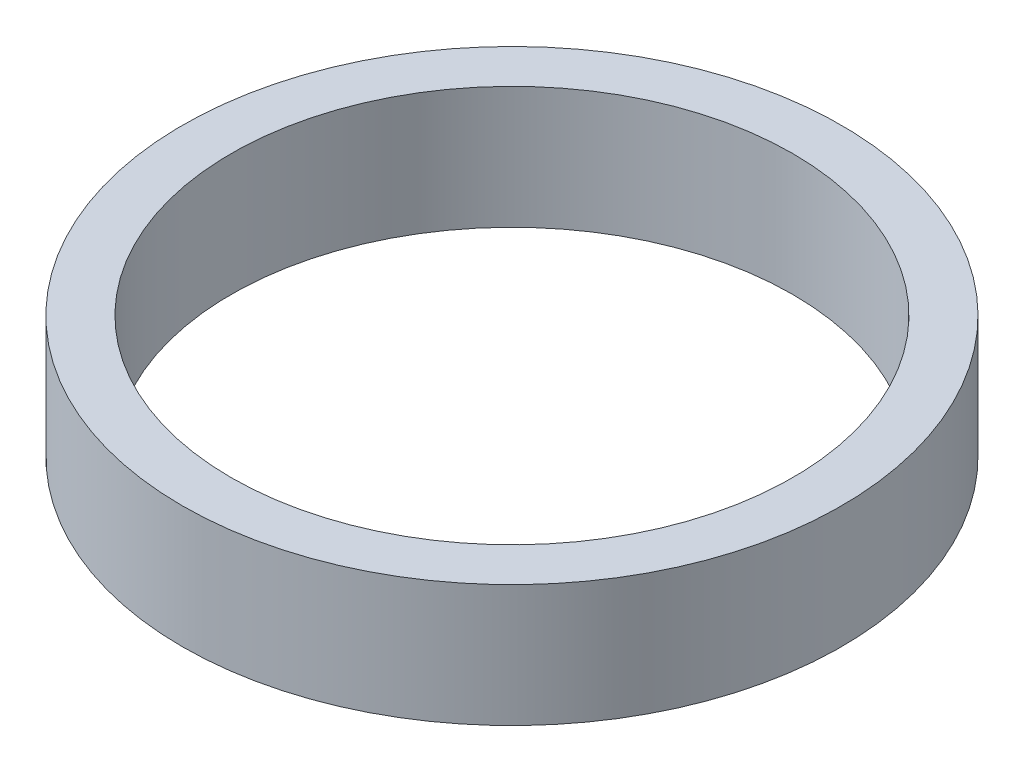
SolidWorks part; units mm, degrees
ref_plane "Front Plane" through (0, 0, 0) normal (0, 0, 1) x (1, 0, 0)
ref_plane "Top Plane" through (0, 0, 0) normal (0, 1, 0) x (1, 0, 0)
ref_plane "Right Plane" through (0, 0, 0) normal (1, 0, 0) x (0, 0, -1)
sketch "Sketch1" plane through (0, 0, 0) normal (0, 1, 0) x (1, 0, 0)
  circle A0 centre (0, 0) radius 13.5
  dimension "D1" = 27
extrude "Boss-Extrude1" add sketch "Sketch1" along normal blind 5
sketch "Sketch2" plane through (0, 5, 0) normal (0, 1, 0) x (1, 0, 0)
  circle A0 centre (0, 0) radius 11.5
  dimension "D1" = 23
extrude "Cut-Extrude1" cut sketch "Sketch2" against normal through all
